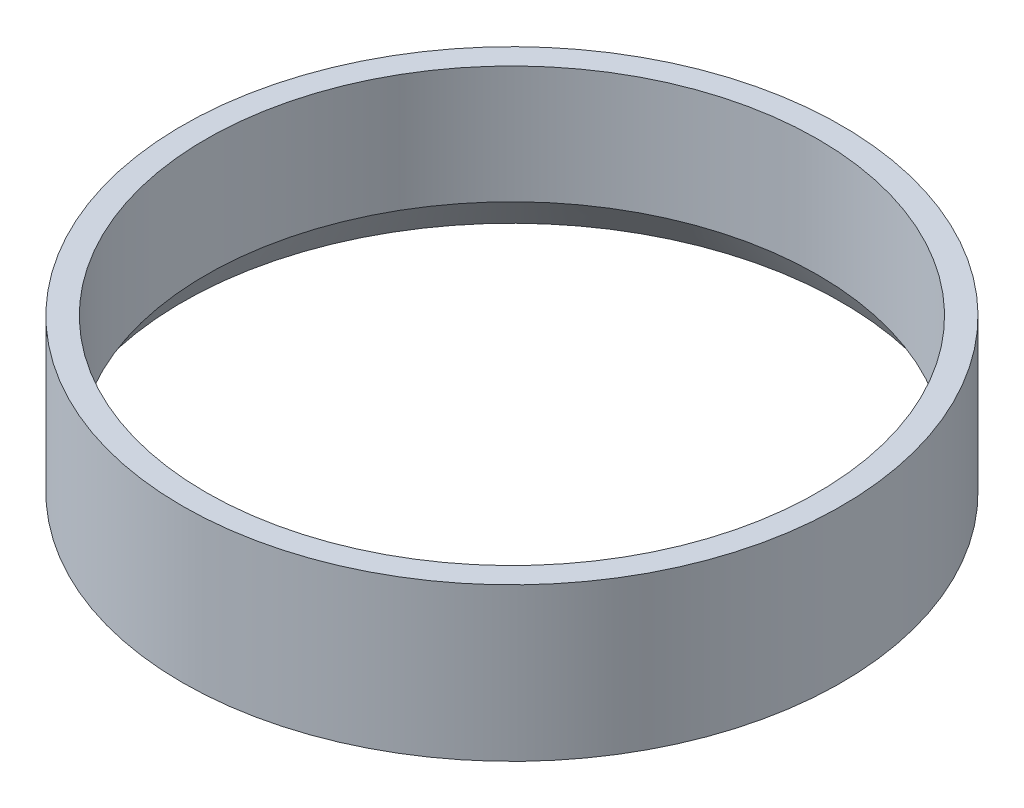
SolidWorks part; units mm, degrees
ref_plane "Спереди" through (0, 0, 0) normal (0, 0, 1) x (1, 0, 0)
ref_plane "Сверху" through (0, 0, 0) normal (0, 1, 0) x (1, 0, 0)
ref_plane "Справа" through (0, 0, 0) normal (1, 0, 0) x (0, 0, -1)
ref_axis "Ось1" through (0, 10, 0) along (0, -1, 0)
sketch "Эскиз1" plane through (0, 0, 0) normal (0, 0, 1) x (1, 0, 0)
  line L9 (26.0083, 0.0055) -> (26, 0.0055)
  line L10 (28.0083, -2.9945) -> (26.0083, 0.0055)
  line L11 (28.0083, -2.9945) -> (26.0083, 0.0055)
  line L12 (26, 0) -> (26, 10) construction
  line L13 (26, 0.0055) -> (26, 10)
  line L14 (28.0083, -2.9945) -> (28.0083, 10)
  line L15 (26, 10) -> (28.0083, 10)
  dimension "D1" = 0.01
revolve "Повернуть1" add sketch "Эскиз1" angle 360 about axis through (0, 10, 0) along (0, -1, 0)
